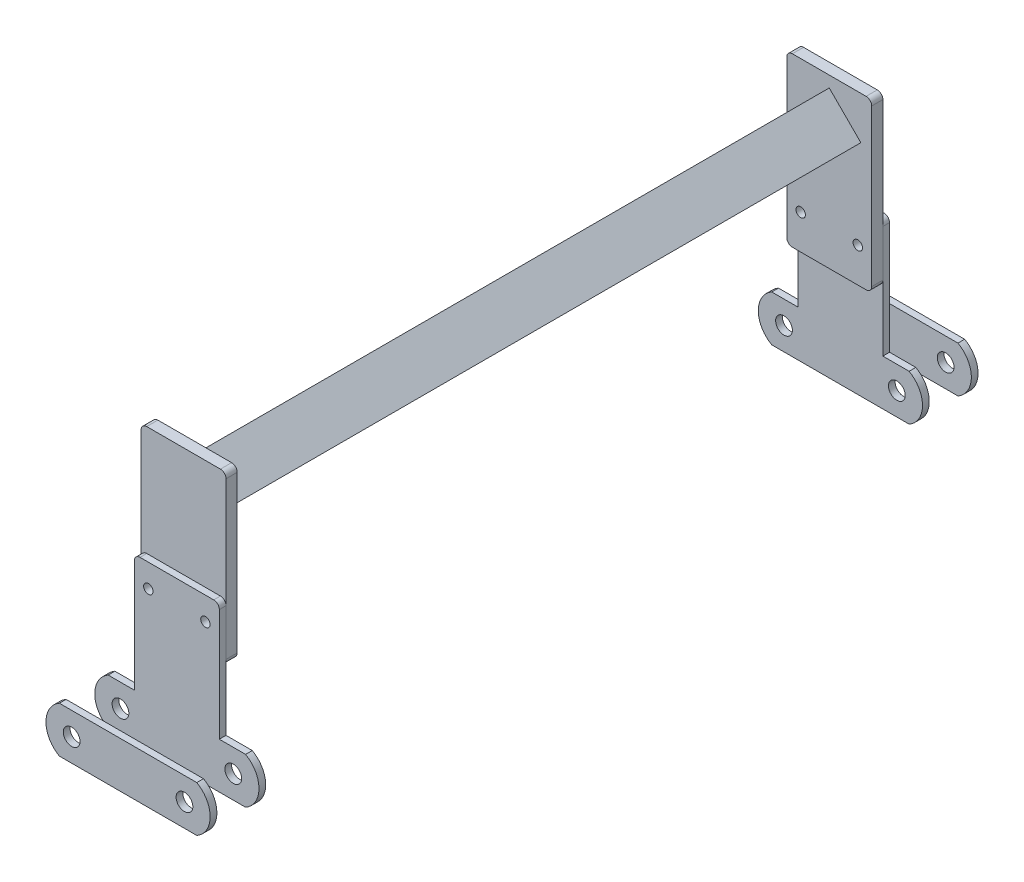
SolidWorks part; units mm, degrees
ref_plane "Front Plane" through (0, 0, 0) normal (0, 0, 1) x (1, 0, 0)
ref_plane "Top Plane" through (0, 0, 0) normal (0, 1, 0) x (1, 0, 0)
ref_plane "Right Plane" through (0, 0, 0) normal (1, 0, 0) x (0, 0, -1)
sketch "Sketch1" plane through (0, 0, 0) normal (0, 0, 1) x (1, 0, 0)
  line L0 (0, 0) -> (75.4353, 0) construction
  line L1 (-61.5, 20.5) -> (61.5, 20.5)
  line L2 (-61.5, -20.5) -> (61.5, -20.5)
  arc A0 (-61.5, 20.5) -> (-61.5, -20.5) centre (-49.9896, 0) ccw
  arc A1 (61.5, -20.5) -> (61.5, 20.5) centre (49.9896, 0) ccw
  point P5 (0, 20.5)
  point P10 (-73.5, 0)
  point P11 (73.5, 0)
  dimension "D1" = 147
  dimension "D2" = 123
  dimension "D3" = 41
extrude "Boss-Extrude1" add sketch "Sketch1" along normal blind 6 from offset 18.85
sketch "Sketch2" plane through (0, 0, 0) normal (0, 0, 1) x (1, 0, 0)
  line L0 (0, 0) -> (0, 37.3705) construction
  circle A0 centre (-50.5, 0) radius 27.5 construction
  circle A1 centre (-50.5, 0) radius 7.5
  circle A2 centre (50.5, 0) radius 7.5
  circle A3 centre (50.5, 0) radius 27.5 construction
  dimension "D1" = 55
  dimension "D2" = 15
  dimension "D3" = 156
extrude "Cut-Extrude1" cut sketch "Sketch2" against normal through all both and the other way through all
mirror "Mirror2" about plane through (0, 0, 0) normal (0, 0, 1) of bodies 102
sketch "Sketch3" plane through (0, 0, -18.85) normal (0, 0, 1) x (1, 0, 0)
  line L0 (-38, 20.5) -> (-38, 126)
  line L1 (61.5, 20.5) -> (-61.5, 20.5) construction
  line L2 (-38, 126) -> (38, 126)
  line L3 (38, 126) -> (38, 20.5)
  line L4 (38, 20.5) -> (-38, 20.5)
  line L5 (-61.5, -20.5) -> (61.5, -20.5) construction
  point P4 (0, 126)
  dimension "D1" = 146.5
  dimension "D2" = 76
extrude "Boss-Extrude2" add sketch "Sketch3" against normal up to surface (6 mm away) up to face at (43, 0, -24.85)
fillet "Fillet1" radius 5 2 edges at (-38, 126, -21.85) (38, 126, -21.85)
sketch "Sketch4" plane through (0, 0, -18.85) normal (0, 0, 1) x (1, 0, 0)
  line L0 (0, 0) -> (0, 81.5526) construction
  line L1 (-61.5, -20.5) -> (61.5, -20.5) construction
  circle A0 centre (-25.55, 105.3) radius 4.2
  circle A1 centre (25.55, 105.3) radius 4.2
  dimension "D1" = 8.4
  dimension "D2" = 59.5
  dimension "D3" = 130
extrude "Cut-Extrude2" cut sketch "Sketch4" against normal through all
sketch "Sketch6" plane through (0, 0, -24.85) normal (0, 0, -1) x (-1, 0, 0)
  line L0 (-38, 74.4) -> (-38, 224.4)
  line L1 (-38, 20.5) -> (-38, 121) construction
  line L2 (-38, 224.4) -> (38, 224.4)
  line L3 (38, 224.4) -> (38, 74.4)
  line L4 (38, 121) -> (38, 20.5) construction
  line L5 (38, 74.4) -> (-38, 74.4)
  line L6 (-33, 126) -> (33, 126) construction
  circle A0 centre (25.55, 105.3) radius 4.2 construction
  circle A1 centre (-25.55, 105.3) radius 4.2 construction
  circle A2 centre (25.55, 105.3) radius 4.2
  circle A3 centre (-25.55, 105.3) radius 4.2
  dimension "D1" = 51.6
  dimension "D2" = 150
extrude "Boss-Extrude4" add sketch "Sketch6" along normal blind 10 separate body
fillet "Fillet2" radius 5 4 edges at (-38, 224.4, -29.85) (38, 224.4, -29.85) (-38, 74.4, -29.85) (38, 74.4, -29.85)
sketch "Sketch7" plane through (0, 0, -24.85) normal (0, 0, 1) x (1, 0, 0)
  line L0 (-33, 224.4) -> (33, 224.4) construction
  line L1 (0, 214.4) -> (-28.2843, 186.1157)
  line L2 (-28.2843, 186.1157) -> (0, 157.8315)
  line L3 (0, 157.8315) -> (28.2843, 186.1157)
  line L4 (28.2843, 186.1157) -> (0, 214.4)
  circle A0 centre (0, 186.1157) radius 20 construction
  point P9 (0, 224.4)
  dimension "D1" = 40
  dimension "D2" = 10
extrude "Boss-Extrude5" add sketch "Sketch7" against normal blind 588
sketch "Sketch8" plane through (0, 0, -612.85) normal (0, 0, -1) x (-1, 0, 0)
  line L4 (38, 79.4) -> (38, 219.4)
  line L5 (33, 224.4) -> (-33, 224.4)
  line L6 (-38, 219.4) -> (-38, 79.4)
  line L7 (-33, 74.4) -> (33, 74.4)
  line L8 (38, 79.4) -> (38, 219.4)
  line L9 (33, 224.4) -> (-33, 224.4)
  line L10 (-38, 219.4) -> (-38, 79.4)
  line L11 (-33, 74.4) -> (33, 74.4)
  circle A0 centre (25.55, 105.3) radius 4.2 construction
  circle A1 centre (-25.55, 105.3) radius 4.2 construction
  circle A2 centre (25.55, 105.3) radius 4.2
  circle A3 centre (-25.55, 105.3) radius 4.2
  arc A4 (38, 219.4) -> (33, 224.4) centre (33, 219.4) ccw
  arc A5 (-33, 224.4) -> (-38, 219.4) centre (-33, 219.4) ccw
  arc A6 (-38, 79.4) -> (-33, 74.4) centre (-33, 79.4) ccw
  arc A7 (33, 74.4) -> (38, 79.4) centre (33, 79.4) ccw
  arc A8 (38, 219.4) -> (33, 224.4) centre (33, 219.4) ccw
  arc A9 (-33, 224.4) -> (-38, 219.4) centre (-33, 219.4) ccw
  arc A10 (-38, 79.4) -> (-33, 74.4) centre (-33, 79.4) ccw
  arc A11 (33, 74.4) -> (38, 79.4) centre (33, 79.4) ccw
  dimension "D1" = 0
extrude "Boss-Extrude6" add sketch "Sketch8" against normal blind 10
ref_plane "Mid_Plane" through (0, 0, -318.85) normal (0, 0, 1) x (1, 0, 0)
mirror "Mirror3" about plane through (0, 0, -318.85) normal (0, 0, 1) of bodies 105 102
delete or keep bodies "Body-Delete/Keep 1" [suppressed] type delete bodies bodies 102 105 110 111
